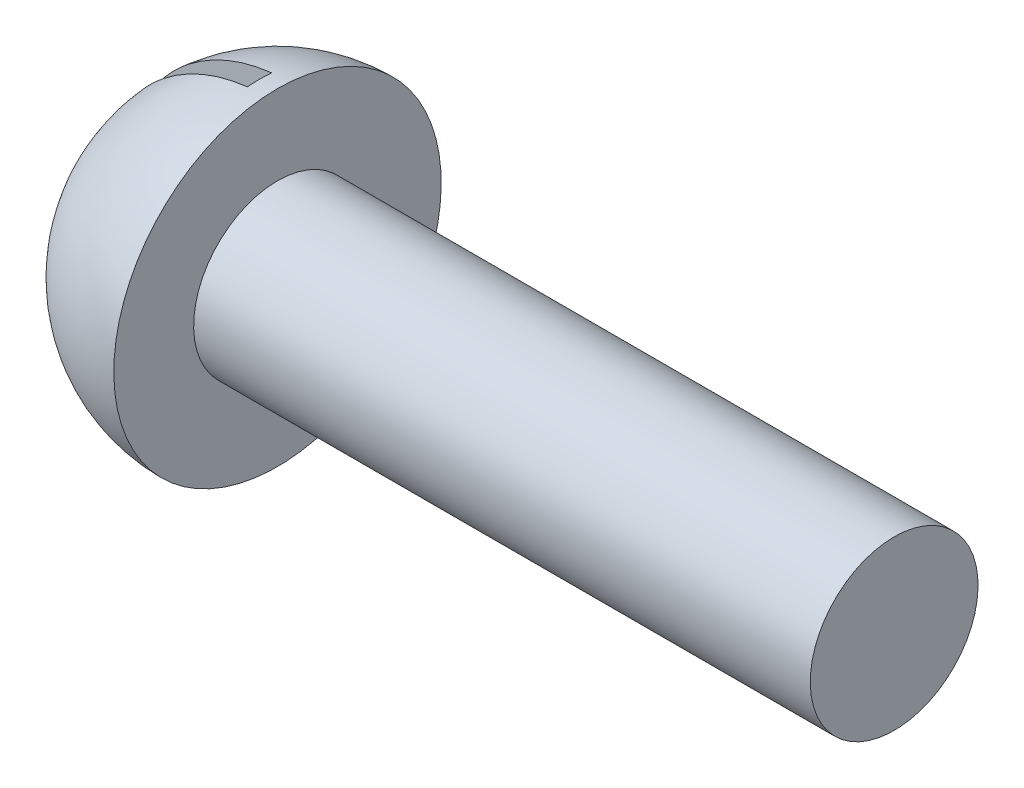
SolidWorks part; units mm, degrees
material "Brass"
ref_plane "Front Plane" through (0, 0, 0) normal (0, 0, 1) x (1, 0, 0)
ref_plane "Top Plane" through (0, 0, 0) normal (0, 1, 0) x (1, 0, 0)
ref_plane "Right Plane" through (0, 0, 0) normal (1, 0, 0) x (0, 0, -1)
sketch "Sketch1" plane through (0, 0, 0) normal (0, 0, 1) x (1, 0, 0)
  line L1 (12.7, 0) -> (12.7, 1.7272)
  line L2 (12.7, 1.7272) -> (0, 1.7272)
  line L3 (0, 3.3715) -> (0, 1.7272)
  line L4 (-3.3715, 0) -> (12.7, 0)
  arc A0 (0, 3.3715) -> (-3.3715, 0) centre (0, 0) ccw
  dimension "D1" = 12.7
  dimension "D2" = 1.7272
ref_axis "Axis2" through (25.3318, 0, 0) along (-1, 0, 0)
revolve "Revolve3" add sketch "Sketch1" angle 360 about axis through (25.3318, 0, 0) along (-1, 0, 0)
ref_plane "Plane1" through (-3.3715, 0, 0) normal (-1, 0, 0) x (0, 0, 1)
sketch "Sketch2" plane through (-3.3715, 0, 0) normal (-1, 0, 0) x (0, 0, 1)
  line L1 (-0.25, 4.3418) -> (0.25, 4.3418)
  line L2 (-0.25, 4.3418) -> (-0.25, -4.4077)
  line L3 (-0.25, -4.4077) -> (0.25, -4.4077)
  line L4 (0.25, 4.3418) -> (0.25, -4.4077)
  point P4 (0, 4.3418)
  dimension "D1" = 0.5
extrude "Cut-Extrude1" cut sketch "Sketch2" against normal blind 3
